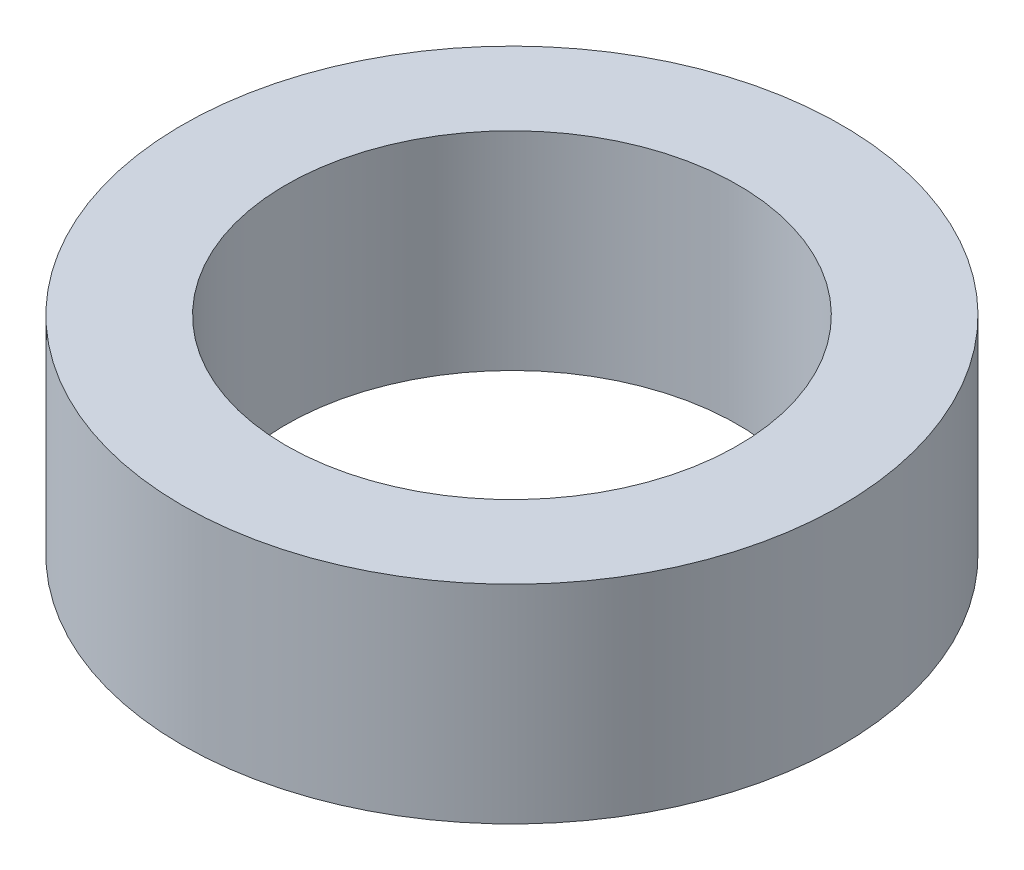
SolidWorks part; units mm, degrees
ref_plane "Front Plane" through (0, 0, 0) normal (0, 0, 1) x (1, 0, 0)
ref_plane "Top Plane" through (0, 0, 0) normal (0, 1, 0) x (1, 0, 0)
ref_plane "Right Plane" through (0, 0, 0) normal (1, 0, 0) x (0, 0, -1)
sketch "Sketch1" plane through (0, 0, 0) normal (0, 1, 0) x (1, 0, 0)
  circle A0 centre (0, 0) radius 3.2639
  circle A1 centre (0, 0) radius 4.7625
  dimension "D1" = 6.5278
  dimension "D2" = 9.525
extrude "Boss-Extrude1" add sketch "Sketch1" along normal blind 3
